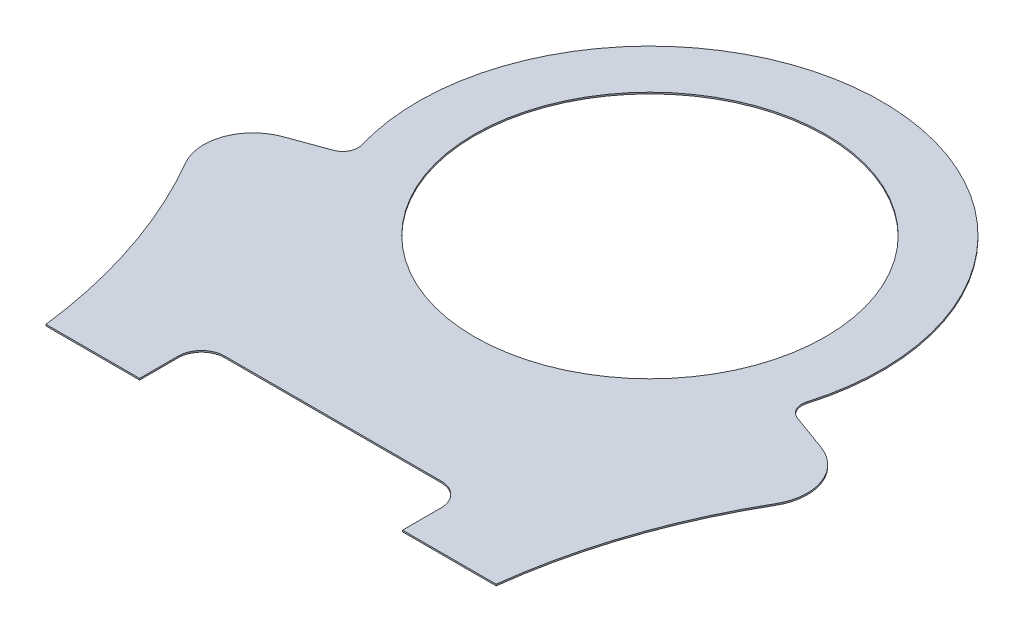
SolidWorks part; units mm, degrees
ref_plane "Front Plane" through (0, 0, 0) normal (0, 0, 1) x (1, 0, 0)
ref_plane "Top Plane" through (0, 0, 0) normal (0, 1, 0) x (1, 0, 0)
ref_plane "Right Plane" through (0, 0, 0) normal (1, 0, 0) x (0, 0, -1)
sketch "Sketch26" plane through (0, 0, 0) normal (0, 1, 0) x (-1, 0, 0)
  line L9 (-17.4129, 6.3378) -> (-15.0057, 5.4616)
  line L11 (15.0057, 5.4616) -> (17.4129, 6.3378)
  line L15 (8.5, 24.5) -> (14.5537, 24.5)
  line L16 (8.5, 22) -> (8.5, 24.5)
  line L17 (-7, 20.5) -> (7, 20.5)
  line L18 (-8.5, 24.5) -> (-8.5, 22)
  line L19 (-14.5537, 24.5) -> (-8.5, 24.5)
  arc A10 (17.4129, 6.3378) -> (19.0848, 10.9443) centre (16.3198, 9.3412) ccw
  arc A11 (-17.4129, 6.3378) -> (-19.0848, 10.9443) centre (-16.3198, 9.3412) cw
  arc A12 (14.5537, 24.5) -> (19.0848, 10.9443) centre (49.7756, 28.738) ccw
  arc A13 (7, 20.5) -> (8.5, 22) centre (7, 22) ccw
  arc A14 (-8.5, 22) -> (-7, 20.5) centre (-7, 22) ccw
  arc A15 (-19.0848, 10.9443) -> (-14.5537, 24.5) centre (-49.7756, 28.738) ccw
  arc A16 (-14.3885, 4.2393) -> (0, -15) centre (0, 0) ccw
  arc A17 (-14.3885, 4.2393) -> (-15.0057, 5.4616) centre (-15.3477, 4.5219) ccw
  circle A18 centre (0, 0) radius 11.35
  arc A20 (15.0057, 5.4616) -> (14.3885, 4.2393) centre (15.3477, 4.5219) ccw
  arc A21 (0, -15) -> (14.3885, 4.2393) centre (0, 0) ccw
extrude "Boss-Extrude1" add sketch "Sketch26" along normal blind 0.096
